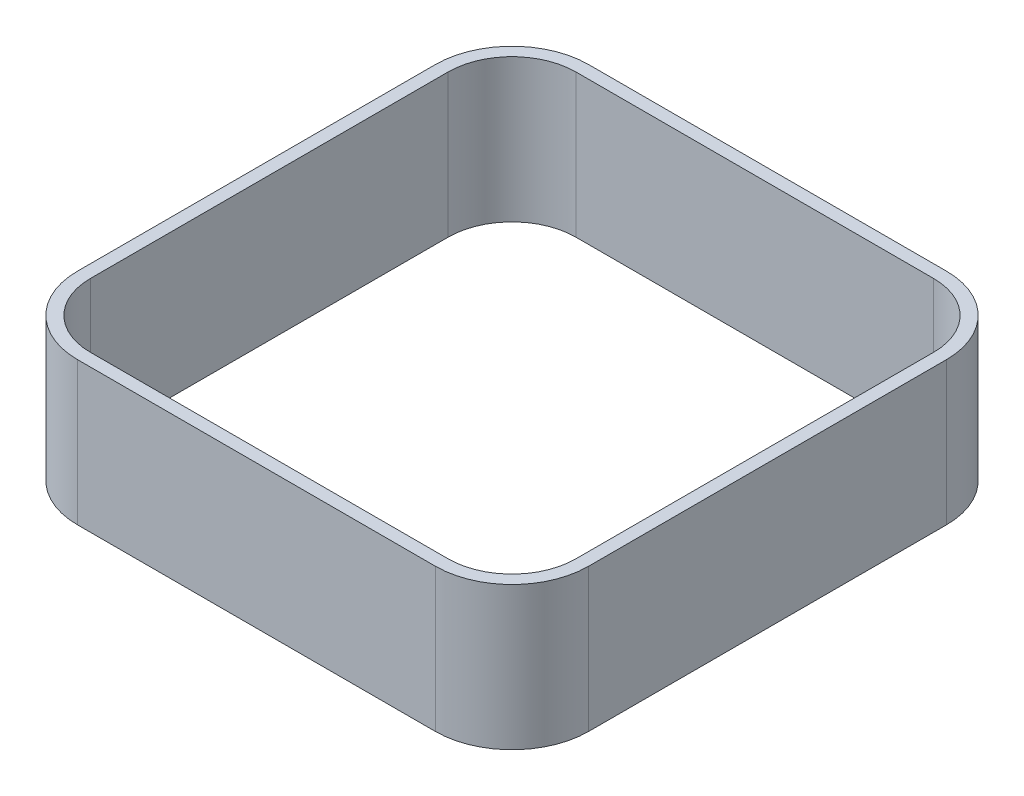
SolidWorks part; units mm, degrees
ref_plane "Front Plane" through (0, 0, 0) normal (0, 0, 1) x (1, 0, 0)
ref_plane "Top Plane" through (0, 0, 0) normal (0, 1, 0) x (1, 0, 0)
ref_plane "Right Plane" through (0, 0, 0) normal (1, 0, 0) x (0, 0, -1)
sketch "Sketch1" plane through (0, 0, 0) normal (0, 1, 0) x (1, 0, 0)
  line L1 (-254, 254) -> (254, 254)
  line L2 (-254, 254) -> (-254, -254)
  line L3 (-254, -254) -> (254, -254)
  line L4 (254, 254) -> (254, -254)
  line L5 (-254, 254) -> (254, -254) construction
  line L6 (-254, -254) -> (254, 254) construction
  point P0 (0, 0)
  dimension "D1" = 508
extrude "Boss-Extrude1" add sketch "Sketch1" along normal blind 142.24
fillet "Fillet1" radius 76.2 4 edges at (-254, 71.12, 254) (-254, 71.12, -254) (254, 71.12, -254) (254, 71.12, 254)
sketch "Sketch2" plane through (0, 142.24, 0) normal (0, 1, 0) x (1, 0, 0)
  line L0 (-241.3, 177.8) -> (-241.3, -177.8)
  line L1 (-177.8, -241.3) -> (177.8, -241.3)
  line L2 (241.3, -177.8) -> (241.3, 177.8)
  line L3 (177.8, 241.3) -> (-177.8, 241.3)
  line L4 (-254, 177.8) -> (-254, -177.8)
  line L5 (-177.8, -254) -> (177.8, -254)
  line L6 (254, -177.8) -> (254, 177.8)
  line L7 (177.8, 254) -> (-177.8, 254)
  line L8 (-254, 177.8) -> (-254, -177.8) construction
  line L9 (-177.8, -254) -> (177.8, -254) construction
  line L10 (254, -177.8) -> (254, 177.8) construction
  line L11 (177.8, 254) -> (-177.8, 254) construction
  arc A0 (-241.3, -177.8) -> (-177.8, -241.3) centre (-177.8, -177.8) ccw
  arc A1 (177.8, -241.3) -> (241.3, -177.8) centre (177.8, -177.8) ccw
  arc A2 (241.3, 177.8) -> (177.8, 241.3) centre (177.8, 177.8) ccw
  arc A3 (-177.8, 241.3) -> (-241.3, 177.8) centre (-177.8, 177.8) ccw
  arc A4 (-254, -177.8) -> (-177.8, -254) centre (-177.8, -177.8) ccw
  arc A5 (177.8, -254) -> (254, -177.8) centre (177.8, -177.8) ccw
  arc A6 (254, 177.8) -> (177.8, 254) centre (177.8, 177.8) ccw
  arc A7 (-177.8, 254) -> (-254, 177.8) centre (-177.8, 177.8) ccw
  arc A8 (-254, -177.8) -> (-177.8, -254) centre (-177.8, -177.8) ccw construction
  arc A9 (177.8, -254) -> (254, -177.8) centre (177.8, -177.8) ccw construction
  arc A10 (254, 177.8) -> (177.8, 254) centre (177.8, 177.8) ccw construction
  arc A11 (-177.8, 254) -> (-254, 177.8) centre (-177.8, 177.8) ccw construction
  dimension "D1" = 0
  dimension "D2" = 12.7
extrude "Cut-Extrude1" cut sketch "Sketch2" against normal up to next
